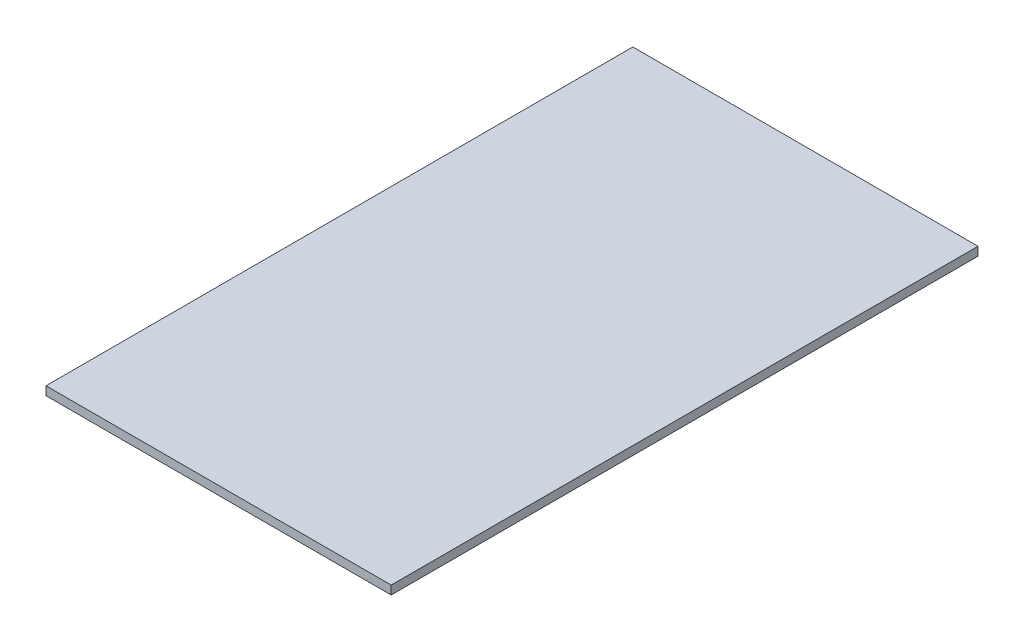
SolidWorks part; units mm, degrees
ref_plane "Front" through (0, 0, 0) normal (0, 0, 1) x (1, 0, 0)
ref_plane "Top" through (0, 0, 0) normal (0, 1, 0) x (1, 0, 0)
ref_plane "Right" through (0, 0, 0) normal (1, 0, 0) x (0, 0, -1)
sketch "Sketch1" plane through (0, 0, 0) normal (0, 1, 0) x (1, 0, 0)
  line L1 (0, 0) -> (127, 0)
  line L2 (0, 0) -> (0, 215.9)
  line L3 (0, 215.9) -> (127, 215.9)
  line L4 (127, 0) -> (127, 215.9)
  dimension "D1" = 215.9
  dimension "D2" = 127
extrude "Boss-Extrude1" add sketch "Sketch1" along normal blind 3.175
